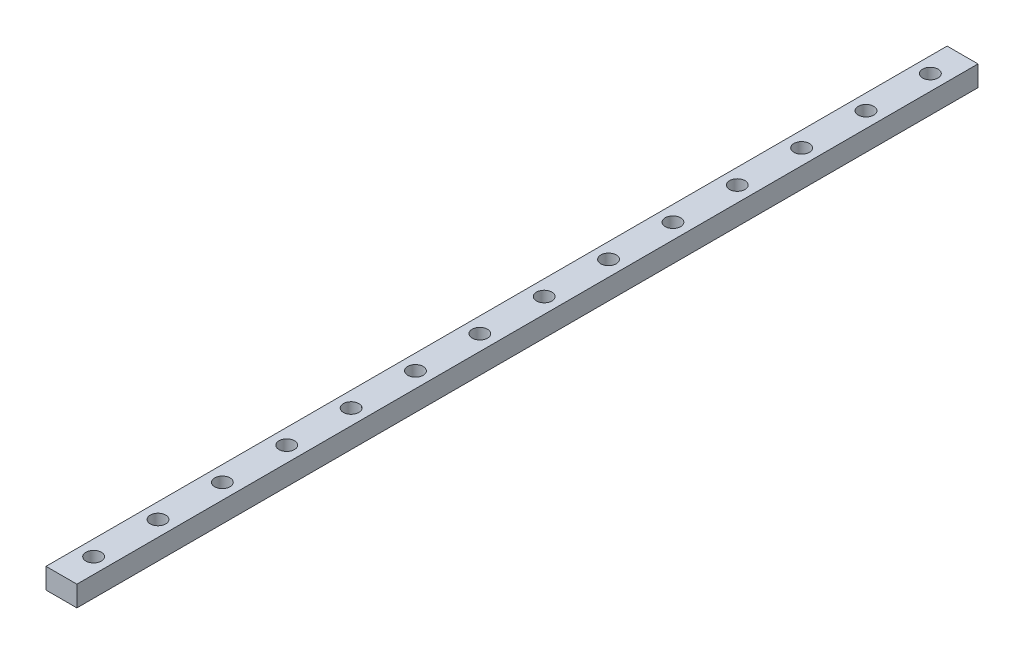
SolidWorks part; units mm, degrees
ref_plane "Front Plane" through (0, 0, 0) normal (0, 0, 1) x (1, 0, 0)
ref_plane "Top Plane" through (0, 0, 0) normal (0, 1, 0) x (1, 0, 0)
ref_plane "Right Plane" through (0, 0, 0) normal (1, 0, 0) x (0, 0, -1)
sketch "Sketch1" plane through (0, 0, 0) normal (0, 0, 1) x (1, 0, 0)
  line L1 (0, 0) -> (12, 0)
  line L2 (0, 0) -> (0, 8)
  line L3 (0, 8) -> (12, 8)
  line L4 (12, 0) -> (12, 8)
  dimension "D1" = 12
  dimension "D2" = 8
extrude "Boss-Extrude1" add sketch "Sketch1" along normal blind 350
sketch "Sketch2" plane through (0, 8, 0) normal (0, 1, 0) x (1, 0, 0)
  line L0 (12, 0) -> (0, 0) construction
  line L1 (0, -350) -> (0, 0) construction
  circle A0 centre (6, -12.5) radius 3
  dimension "D1" = 6
  dimension "D2" = 12.5
  dimension "D3" = 6
extrude "Cut-Extrude1" cut sketch "Sketch2" against normal blind 4.5
sketch "Sketch4" plane through (0, 0, 0) normal (0, -1, 0) x (1, 0, 0)
  line L0 (0, 350) -> (0, 0) construction
  line L1 (0, 0) -> (12, 0) construction
  circle A0 centre (6, 12.5) radius 1.75
  dimension "D1" = 3.5
  dimension "D2" = 6
  dimension "D3" = 12.5
extrude "Cut-Extrude2" cut sketch "Sketch4" against normal through all
pattern_linear "LPattern2" count 14 spacing 25 along (0, 0, 1) of "Cut-Extrude1", "Cut-Extrude2"
